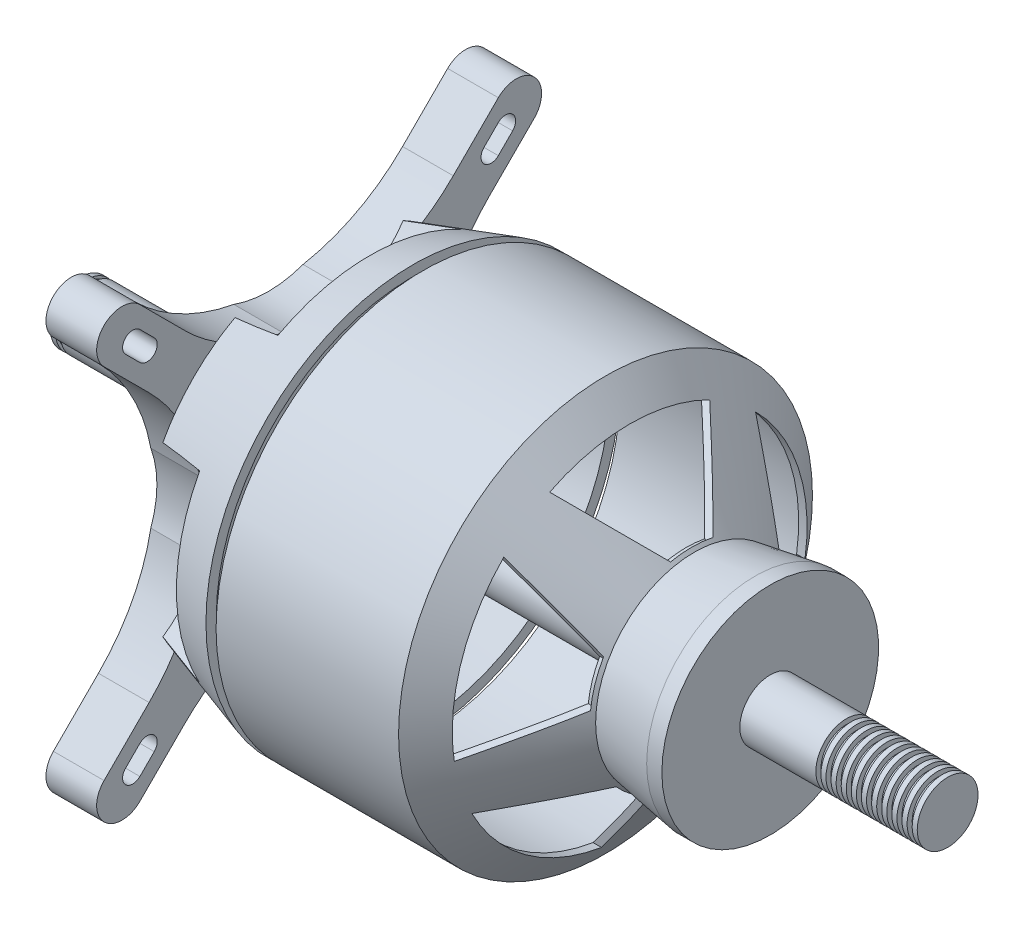
SolidWorks part; units mm, degrees
ref_plane "Front Plane" through (0, 0, 0) normal (0, 0, 1) x (1, 0, 0)
ref_plane "Top Plane" through (0, 0, 0) normal (0, 1, 0) x (1, 0, 0)
ref_plane "Right Plane" through (0, 0, 0) normal (1, 0, 0) x (0, 0, -1)
sketch "Sketch1" plane through (0, 0, 0) normal (0, 0, 1) x (1, 0, 0)
  line L0 (0, 0) -> (171, 0)
  line L1 (0, 0) -> (0, 6)
  line L2 (0, 6) -> (1, 6)
  line L3 (1, 6) -> (1, 5.5)
  line L4 (1, 5.5) -> (2, 5.5)
  line L5 (2, 5.5) -> (2, 6)
  line L6 (2, 6) -> (47, 6)
  line L7 (47, 6) -> (47, 35)
  line L8 (65.5, 40.83) -> (65.5, 38.83)
  line L9 (65.5, 38.83) -> (65.5, 38.7881)
  line L10 (67.5, 38.83) -> (67.5, 40.83)
  line L11 (65.5, 40.83) -> (47, 35)
  line L12 (67.5, 40.83) -> (103.5, 40.83)
  line L16 (121, 19.45) -> (103.5, 40.83)
  line L17 (136, 21.38) -> (136, 6)
  line L18 (151, 6) -> (151, 5)
  line L19 (151, 5) -> (152, 5)
  line L20 (152, 5) -> (152, 6)
  line L21 (133, 21.38) -> (121, 19.45)
  line L22 (133, 21.38) -> (136, 21.38)
  line L23 (152, 6) -> (153, 6)
  line L24 (153, 5) -> (154, 5)
  line L25 (136, 6) -> (151, 6)
  line L26 (153, 6) -> (153, 5)
  line L27 (154, 5) -> (154, 6)
  line L28 (154, 6) -> (155, 6)
  line L29 (155, 5) -> (156, 5)
  line L30 (155, 6) -> (155, 5)
  line L31 (156, 5) -> (156, 6)
  line L32 (156, 6) -> (157, 6)
  line L33 (157, 5) -> (158, 5)
  line L34 (157, 6) -> (157, 5)
  line L35 (158, 5) -> (158, 6)
  line L36 (158, 6) -> (159, 6)
  line L37 (159, 5) -> (160, 5)
  line L38 (159, 6) -> (159, 5)
  line L39 (160, 5) -> (160, 6)
  line L40 (160, 6) -> (161, 6)
  line L41 (161, 5) -> (162, 5)
  line L42 (161, 6) -> (161, 5)
  line L43 (162, 5) -> (162, 6)
  line L44 (162, 6) -> (163, 6)
  line L45 (163, 5) -> (164, 5)
  line L46 (163, 6) -> (163, 5)
  line L47 (164, 5) -> (164, 6)
  line L48 (164, 6) -> (165, 6)
  line L49 (165, 5) -> (166, 5)
  line L50 (165, 6) -> (165, 5)
  line L51 (166, 5) -> (166, 6)
  line L52 (166, 6) -> (167, 6)
  line L53 (167, 5) -> (168, 5)
  line L54 (167, 6) -> (167, 5)
  line L55 (168, 5) -> (168, 6)
  line L56 (168, 6) -> (169, 6)
  line L57 (169, 5) -> (170, 5)
  line L58 (169, 6) -> (169, 5)
  line L59 (170, 5) -> (170, 6)
  line L60 (170, 6) -> (171, 6)
  line L61 (171, 6) -> (171, 0)
  line L62 (47, 6) -> (136, 6)
  line L63 (133, 6) -> (133, 19.45)
  line L64 (133, 19.45) -> (121, 17.4973)
  line L65 (121, 17.4973) -> (103.5, 38.7881)
  line L66 (103.5, 38.7881) -> (67.5, 38.7881)
  line L67 (65.5, 38.7881) -> (53.333, 35)
  line L68 (53.333, 35) -> (49.6555, 33.855)
  line L69 (49.6555, 33.855) -> (49.6555, 6)
  line L70 (67.5, 38.83) -> (67.5, 38.7881)
revolve "Revolve1" add sketch "Sketch1" angle 360 about L0
sketch "Sketch5" plane through (47, 0, 0) normal (-1, 0, 0) x (0, 0, 1)
  circle A1 centre (0, 0) radius 42
  circle A2 centre (0, 42) radius 20
extrude "Cut-Extrude1" cut sketch "Sketch5" against normal blind 10 contours A2
pattern_circular "CirPattern2" count 4 over 360 about axis through (0, 0, 0) along (1, 0, 0) of "Cut-Extrude1"
sketch "Sketch6" plane through (47, 0, 0) normal (-1, 0, 0) x (0, 0, 1)
  line L7 (-42.4264, 35.3553) -> (-33.5355, 26.4645)
  line L8 (42.4264, -35.3553) -> (33.5355, -26.4645)
  line L9 (-42.4264, -35.3553) -> (-33.5355, -26.4645)
  line L10 (-35.3553, -42.4264) -> (-26.4645, -33.5355)
  line L11 (33.5355, 26.4645) -> (42.4264, 35.3553)
  line L13 (26.4645, 33.5355) -> (35.3553, 42.4264)
  line L14 (-26.4645, 33.5355) -> (-35.3553, 42.4264)
  line L20 (26.4645, -33.5355) -> (35.3553, -42.4264)
  circle A0 centre (0, 0) radius 60
  arc A5 (35.3553, -42.4264) -> (42.4264, -35.3553) centre (38.8909, -38.8909) ccw
  arc A6 (-42.4264, -35.3553) -> (-35.3553, -42.4264) centre (-38.8909, -38.8909) ccw
  arc A7 (-35.3553, 42.4264) -> (-42.4264, 35.3553) centre (-38.8909, 38.8909) ccw
  arc A8 (42.4264, 35.3553) -> (35.3553, 42.4264) centre (38.8909, 38.8909) ccw
  arc A9 (-26.4645, 33.5355) -> (26.4645, 33.5355) centre (0, 60) ccw
  arc A10 (33.5355, 26.4645) -> (33.5355, -26.4645) centre (60, 0) ccw
  arc A11 (26.4645, -33.5355) -> (-26.4645, -33.5355) centre (0, -60) ccw
  arc A12 (-33.5355, -26.4645) -> (-33.5355, 26.4645) centre (-60, 0) ccw
  point P25 (0, 0)
  point P35 (0, 0)
  dimension "D1" = 4
  dimension "D2" = 4
extrude "Boss-Extrude3" add sketch "Sketch6" along normal blind 10
sketch "Sketch7" plane through (37, 0, 0) normal (-1, 0, 0) x (0, 0, 1)
  line L1 (-32.5269, 35.3553) -> (35.3553, 35.3553)
  line L2 (35.3553, 35.3553) -> (35.3553, -35.3553)
  line L3 (35.3553, -35.3553) -> (-35.3553, -35.3553)
  line L4 (-35.3553, -35.3553) -> (-35.3553, 32.5269)
  line L5 (-35.3553, 38.1838) -> (-32.5269, 35.3553)
  line L6 (-38.1838, 35.3553) -> (-35.3553, 32.5269)
  line L8 (-35.3553, 38.1838) -> (-32.5269, 35.3553)
  arc A1 (-35.3553, 38.1838) -> (-38.1838, 35.3553) centre (-36.7696, 36.7696) ccw
  arc A2 (-32.5269, 35.3553) -> (-35.3553, 32.5269) centre (-33.9411, 33.9411) cw
extrude "Cut-Extrude2" cut sketch "Sketch7" against normal blind 10 contours A2 L5 A1 L6
pattern_circular "CirPattern3" count 4 over 360 about axis through (0, 0, 0) along (1, 0, 0) of "Cut-Extrude2"
sketch "Sketch8" plane through (37, 0, 0) normal (-1, 0, 0) x (0, 0, 1)
  line L0 (0, 0.6542) -> (20.53, 21.1842)
  circle A0 centre (0, 0) radius 29.5
  circle A1 centre (20.53, 21.1842) radius 2
extrude "Cut-Extrude3" cut sketch "Sketch8" against normal blind 20 contours A1
pattern_circular "CirPattern4" count 4 over 360 about axis through (0, 0, 0) along (1, 0, 0) of "Cut-Extrude3"
sketch "Sketch9" plane through (67.5, 0, 0) normal (-1, 0, 0) x (0, 0, 1)
  line L2 (-4, 19.45) -> (-15.7872, 31.2372)
  line L3 (4, 19.45) -> (15.7872, 31.2372)
  line L4 (4, 19.45) -> (3.6537, 19.1037)
  line L5 (-4, 19.45) -> (-3.6537, 19.1037)
  circle A0 centre (0, 0) radius 19.45
  circle A1 centre (0, 0) radius 35
extrude "Cut-Extrude4" cut sketch "Sketch9" against normal blind 53 contours L3 A1 L2 L5 A0 L4
pattern_circular "CirPattern5" count 5 over 360 about axis through (0, 0, 0) along (-1, 0, 0) of "Cut-Extrude4"
sketch "Sketch10" plane through (37, 0, 0) normal (-1, 0, 0) x (0, 0, 1)
  circle A0 centre (-21.1842, 20.53) radius 2.5
extrude "Cut-Extrude5" cut sketch "Sketch10" against normal blind 20
pattern_circular "CirPattern6" count 4 over 360 about axis through (0, 0, 0) along (1, 0, 0) of "Cut-Extrude5"
